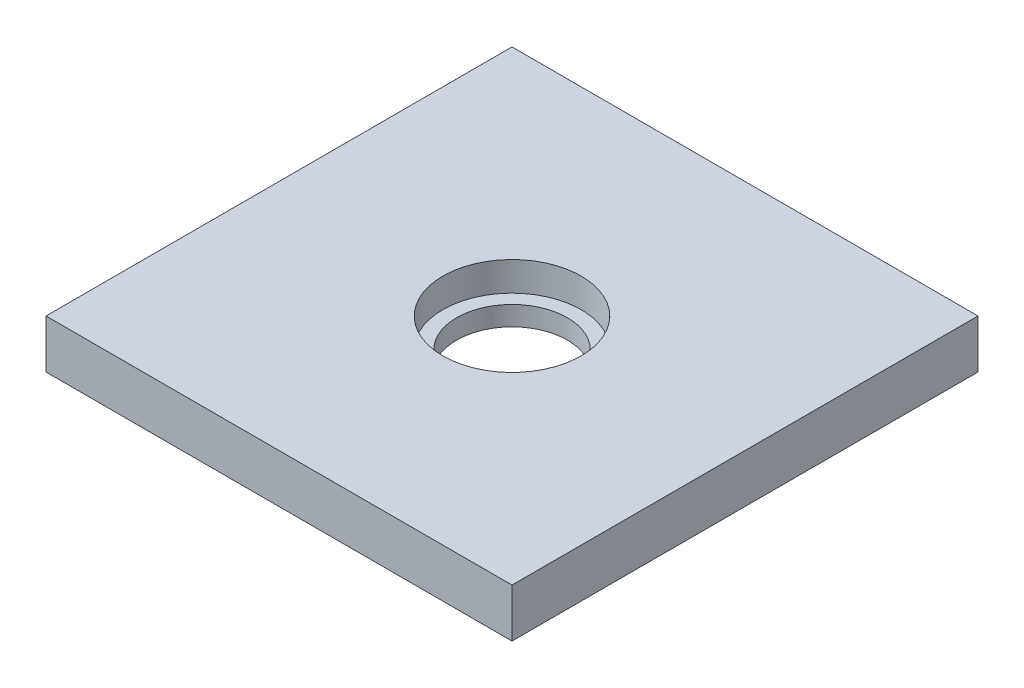
SolidWorks part; units mm, degrees
material "6061-O (SS)"
ref_plane "Front Plane" through (0, 0, 0) normal (0, 0, 1) x (1, 0, 0)
ref_plane "Top Plane" through (0, 0, 0) normal (0, 1, 0) x (1, 0, 0)
ref_plane "Right Plane" through (0, 0, 0) normal (1, 0, 0) x (0, 0, -1)
sketch "Sketch1" plane through (0, 0, 0) normal (0, 0, 1) x (1, 0, 0)
  line L7 (-76.2, -7.9375) -> (76.2, -7.9375)
  line L8 (-76.2, -7.9375) -> (-76.2, 7.9375)
  line L9 (-76.2, 7.9375) -> (76.2, 7.9375)
  line L10 (76.2, -7.9375) -> (76.2, 7.9375)
  line L11 (-76.2, -7.9375) -> (76.2, 7.9375) construction
  line L12 (-76.2, 7.9375) -> (76.2, -7.9375) construction
  point P4 (0, 0)
  point P14 (0, 0)
  dimension "Thickness" = 15.875
  dimension "Width" = 152.4
sketch "Sketch2" plane through (0, 0, 0) normal (0, 1, 0) x (0, 0, -1)
  line L0 (76.2, 76.2) -> (-76.2, 76.2) construction
  point P4 (0, 76.2)
  dimension "Length" = 152.4
sketch "Sketch3" plane through (0, 0, 0) normal (0, 0, 1) x (1, 0, 0)
  line L6 (-76.2, 7.9375) -> (76.2, 7.9375)
  line L7 (76.2, 7.9375) -> (76.2, -7.9375)
  line L8 (76.2, -7.9375) -> (-76.2, -7.9375)
  line L9 (-76.2, -7.9375) -> (-76.2, 7.9375)
extrude "Boss-Extrude1" add sketch "Sketch3" along normal mid plane 152.4
sketch "Sketch4" plane through (0, 7.9375, 0) normal (0, 1, 0) x (1, 0, 0)
  circle A0 centre (0, 0) radius 22.6219
  dimension "D1" = 45.2437
extrude "Cut-Extrude1" cut sketch "Sketch4" against normal blind 9.525
sketch "Sketch5" plane through (0, -1.5875, 0) normal (0, 1, 0) x (1, 0, 0)
  circle A0 centre (0, 0) radius 18.0975
  dimension "D1" = 36.195
extrude "Cut-Extrude2" cut sketch "Sketch5" against normal through all
equation "\"D1@Boss-Extrude1\" = \"Length@Sketch2\""
